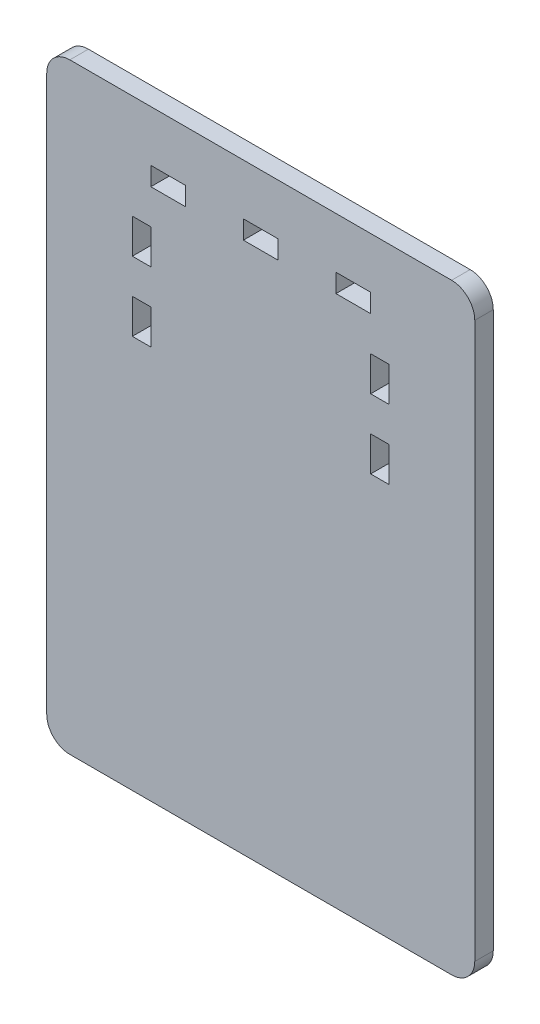
SolidWorks part; units mm, degrees
material "Beech"
ref_plane "Front" through (0, 0, 0) normal (0, 0, 1) x (1, 0, 0)
ref_plane "Top" through (0, 0, 0) normal (0, 1, 0) x (1, 0, 0)
ref_plane "Right" through (0, 0, 0) normal (1, 0, 0) x (0, 0, -1)
sketch "Sketch1" plane through (0, 0, 0) normal (0, 0, 1) x (1, 0, 0)
  line L1 (-82.5, -130) -> (82.5, -130)
  line L2 (-92.5, -120) -> (-92.5, 120)
  line L3 (-82.5, 130) -> (82.5, 130)
  line L4 (92.5, -120) -> (92.5, 120)
  line L5 (-92.5, -130) -> (92.5, 130) construction
  line L6 (-92.5, 130) -> (92.5, -130) construction
  arc A0 (-82.5, -130) -> (-92.5, -120) centre (-82.5, -120) cw
  arc A1 (82.5, -130) -> (92.5, -120) centre (82.5, -120) ccw
  arc A2 (82.5, 130) -> (92.5, 120) centre (82.5, 120) cw
  arc A3 (-92.5, 120) -> (-82.5, 130) centre (-82.5, 120) cw
  point P0 (0, 0)
  dimension "D3" = 10
  dimension "D1" = 260
  dimension "D2" = 185
extrude "Boss-Extrude1" add sketch "Sketch1" along normal blind 8
sketch "Sketch2" plane through (0, 0, 8) normal (0, 0, 1) x (1, 0, 0)
  line L0 (7.5, 100) -> (-7.5, 100)
  line L1 (-47.5, 108) -> (-32.5, 108)
  line L2 (-47.5, 108) -> (-47.5, 100)
  line L3 (-47.5, 100) -> (-32.5, 100)
  line L4 (-32.5, 108) -> (-32.5, 100)
  line L5 (-47.5, 108) -> (-32.5, 100) construction
  line L6 (-47.5, 100) -> (-32.5, 108) construction
  line L7 (-7.5, 100) -> (-7.5, 108)
  line L8 (-7.5, 108) -> (7.5, 108)
  line L9 (0, 108) -> (0, 100) construction
  line L10 (32.5, 108) -> (32.5, 100)
  line L11 (47.5, 108) -> (32.5, 108)
  line L12 (47.5, 108) -> (47.5, 100)
  line L13 (47.5, 100) -> (32.5, 100)
  line L14 (7.5, 100) -> (7.5, 108)
  line L16 (-47.5, 55) -> (-47.5, 40)
  line L17 (-47.5, 85) -> (-55.5, 85)
  line L18 (-47.5, 85) -> (-47.5, 70)
  line L19 (-47.5, 70) -> (-55.5, 70)
  line L20 (-55.5, 85) -> (-55.5, 70)
  line L21 (-47.5, 85) -> (-55.5, 70) construction
  line L22 (-47.5, 70) -> (-55.5, 85) construction
  line L23 (-47.5, 40) -> (-55.5, 40)
  line L24 (-55.5, 55) -> (-55.5, 40)
  line L25 (-47.5, 55) -> (-55.5, 55)
  line L26 (47.5, 55) -> (55.5, 55)
  line L27 (55.5, 55) -> (55.5, 40)
  line L28 (47.5, 40) -> (55.5, 40)
  line L29 (47.5, 55) -> (47.5, 40)
  line L30 (47.5, 70) -> (55.5, 70)
  line L31 (55.5, 85) -> (55.5, 70)
  line L32 (47.5, 85) -> (55.5, 85)
  line L33 (47.5, 85) -> (47.5, 70)
  point P0 (-40, 104)
  point P23 (-51.5, 77.5)
  dimension "D2" = 7.5
  dimension "D1" = 100
  dimension "D3" = 15
  dimension "D4" = 8
  dimension "D5" = 25
  dimension "D6" = 8
  dimension "D7" = 15
  dimension "D8" = 15
  dimension "D10" = 15
  dimension "D9" = 2
extrude "Cut-Extrude1" cut sketch "Sketch2" against normal through all
